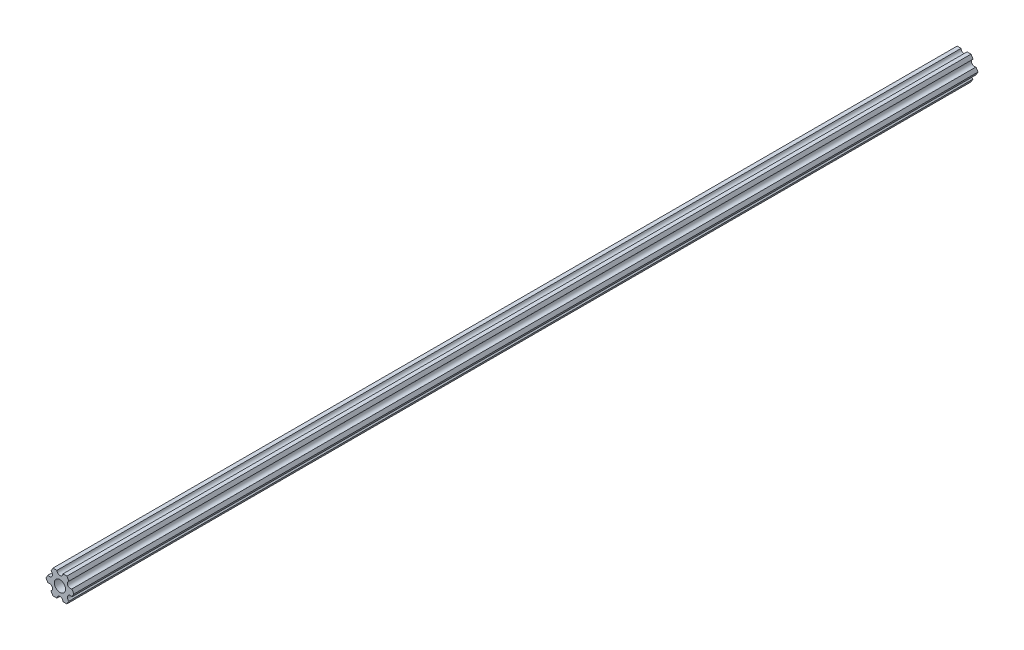
SolidWorks part; units mm, degrees
ref_plane "Front Plane" through (0, 0, 0) normal (0, 0, 1) x (1, 0, 0)
ref_plane "Top Plane" through (0, 0, 0) normal (0, 1, 0) x (1, 0, 0)
ref_plane "Right Plane" through (0, 0, 0) normal (1, 0, 0) x (0, 0, -1)
ref_plane "Plane1" through (0, 0, 231.775) normal (0, 0, 1) x (1, 0, 0)
sketch "Sketch1" plane through (0, 0, 231.775) normal (0, 0, 1) x (1, 0, 0)
  line L0 (6.293, -1.8002) -> (7.3323, 0)
  line L1 (7.3323, 0) -> (6.293, 1.8002)
  line L2 (4.7055, 4.5498) -> (3.6662, 6.35)
  line L3 (3.6662, 6.35) -> (1.5875, 6.35)
  line L4 (-1.5875, 6.35) -> (-3.6662, 6.35)
  line L5 (-3.6662, 6.35) -> (-4.7055, 4.5498)
  line L6 (-6.293, 1.8002) -> (-7.3323, 0)
  line L7 (-7.3323, 0) -> (-6.293, -1.8002)
  line L8 (-4.7055, -4.5498) -> (-3.6662, -6.35)
  line L9 (-3.6662, -6.35) -> (-1.5875, -6.35)
  line L10 (1.5875, -6.35) -> (3.6662, -6.35)
  line L11 (3.6662, -6.35) -> (4.7055, -4.5498)
  arc A0 (6.293, 1.8002) -> (4.7055, 4.5498) centre (5.4993, 3.175) cw
  arc A1 (1.5875, 6.35) -> (-1.5875, 6.35) centre (0, 6.35) cw
  arc A2 (-4.7055, 4.5498) -> (-6.293, 1.8002) centre (-5.4993, 3.175) cw
  arc A3 (-6.293, -1.8002) -> (-4.7055, -4.5498) centre (-5.4993, -3.175) cw
  arc A4 (-1.5875, -6.35) -> (1.5875, -6.35) centre (0, -6.35) cw
  arc A5 (4.7055, -4.5498) -> (6.293, -1.8002) centre (5.4993, -3.175) cw
  circle A6 centre (0, 0) radius 2.9337
extrude "Boss-Extrude1" add sketch "Sketch1" against normal blind 463.55
other "Move Face1" face at (-2.9337, 0, 231.775) parameters "D1"=12.7
